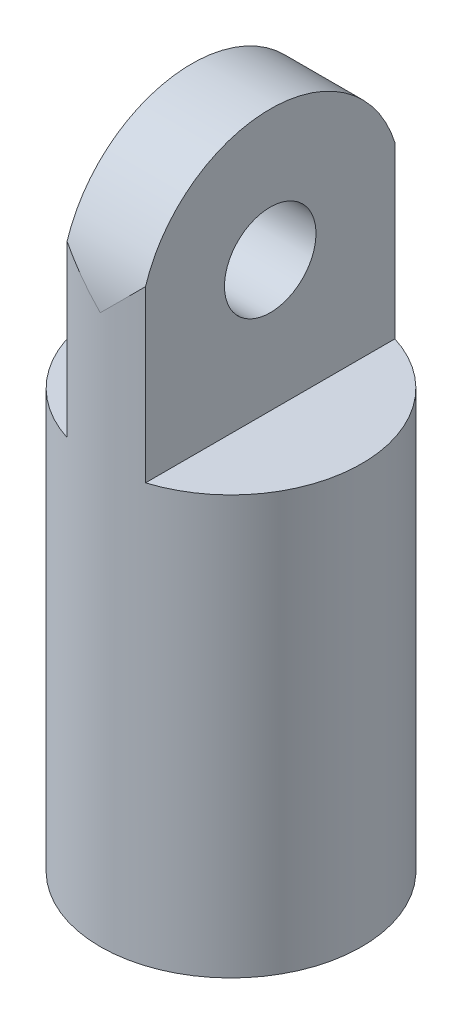
SolidWorks part; units mm, degrees
ref_plane "Front Plane" through (0, 0, 0) normal (0, 0, 1) x (1, 0, 0)
ref_plane "Top Plane" through (0, 0, 0) normal (0, 1, 0) x (1, 0, 0)
ref_plane "Right Plane" through (0, 0, 0) normal (1, 0, 0) x (0, 0, -1)
sketch "Sketch1" plane through (0, 0, 0) normal (0, 1, 0) x (1, 0, 0)
  circle A0 centre (0, 0) radius 3.1
  circle A1 centre (0, 0) radius 5
  dimension "D1" = 6.2
  dimension "D2" = 10
extrude "Boss-Extrude1" add sketch "Sketch1" along normal blind 15
sketch "Sketch2" plane through (0, 15, 0) normal (0, 1, 0) x (1, 0, 0)
  circle A0 centre (0, 0) radius 5
extrude "Boss-Extrude2" add sketch "Sketch2" along normal blind 1
sketch "Sketch4" plane through (0, 16, 0) normal (0, 1, 0) x (1, 0, 0)
  line L0 (-1.5, 4.7697) -> (-1.5, -4.7697)
  line L1 (0, -5.5) -> (0, 5.5) construction
  line L2 (1.5, 4.7697) -> (1.5, -4.7697)
  arc A0 (-1.5, -4.7697) -> (1.5, -4.7697) centre (0, 0) ccw
  arc A1 (1.5, 4.7697) -> (-1.5, 4.7697) centre (0, 0) ccw
  circle A2 centre (0, 0) radius 5 construction
  dimension "D1" = 3
extrude "Boss-Extrude3" add sketch "Sketch4" along normal blind 10
sketch "Sketch5" plane through (-1.5, 0, 0) normal (-1, 0, 0) x (0, 0, 1)
  line L0 (0, -5.5) -> (0, 5.5) construction
  line L1 (-4.7697, 26) -> (4.7697, 26) construction
  circle A0 centre (0, 21) radius 1.75
  dimension "D2" = 3.5
  dimension "D1" = 5
extrude "Cut-Extrude1" cut sketch "Sketch5" against normal through all
sketch "Sketch6" plane through (0, 0, 0) normal (1, 0, 0) x (0, 0, -1)
  line L0 (-5, 21) -> (-5, 26.952)
  line L1 (-5, 26.952) -> (5, 26.952)
  line L2 (5, 26.952) -> (5, 21)
  arc A0 (5, 21) -> (-5, 21) centre (0, 21) ccw
extrude "Cut-Extrude2" cut sketch "Sketch6" against normal through all both and the other way through all
